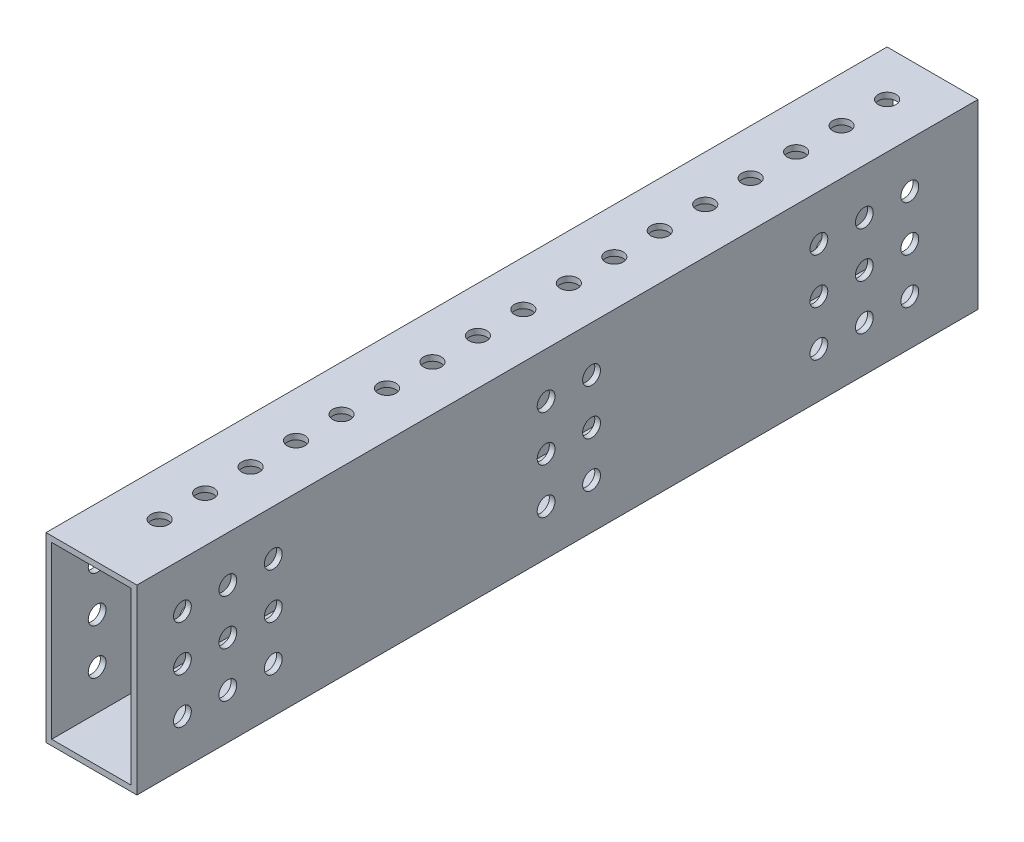
SolidWorks part; units mm, degrees
material "6061-T6 (SS)"
ref_plane "Front Plane" through (0, 0, 0) normal (0, 0, 1) x (1, 0, 0)
ref_plane "Top Plane" through (0, 0, 0) normal (0, 1, 0) x (1, 0, 0)
ref_plane "Right Plane" through (0, 0, 0) normal (1, 0, 0) x (0, 0, -1)
sketch "Sketch1" plane through (0, 0, 0) normal (1, 0, 0) x (0, 0, -1)
  line L0 (12.7, 50.8) -> (12.7, 0) construction
  line L1 (0, 0) -> (234.95, 0)
  line L2 (0, 0) -> (0, 50.8)
  line L3 (0, 50.8) -> (234.95, 50.8)
  line L4 (234.95, 0) -> (234.95, 50.8)
  line L5 (12.7, 12.7) -> (25.4, 12.7) construction
  circle A0 centre (12.7, 25.4) radius 2.4892
  circle A1 centre (12.7, 38.1) radius 2.4892
  circle A2 centre (12.7, 12.7) radius 2.4892
  circle A3 centre (25.4, 12.7) radius 2.4892
  circle A4 centre (25.4, 25.4) radius 2.4892
  circle A5 centre (25.4, 38.1) radius 2.4892
  circle A6 centre (38.1, 12.7) radius 2.4892
  circle A7 centre (38.1, 25.4) radius 2.4892
  circle A8 centre (38.1, 38.1) radius 2.4892
  circle A24 centre (114.3, 12.7) radius 2.4892
  circle A25 centre (114.3, 25.4) radius 2.4892
  circle A26 centre (114.3, 38.1) radius 2.4892
  circle A27 centre (127, 12.7) radius 2.4892
  circle A28 centre (127, 25.4) radius 2.4892
  circle A29 centre (127, 38.1) radius 2.4892
  circle A42 centre (190.5, 12.7) radius 2.4892
  circle A43 centre (190.5, 25.4) radius 2.4892
  circle A44 centre (190.5, 38.1) radius 2.4892
  circle A45 centre (203.2, 12.7) radius 2.4892
  circle A46 centre (203.2, 25.4) radius 2.4892
  circle A47 centre (203.2, 38.1) radius 2.4892
  circle A48 centre (215.9, 12.7) radius 2.4892
  circle A49 centre (215.9, 25.4) radius 2.4892
  circle A50 centre (215.9, 38.1) radius 2.4892
  circle A51 centre (50.8, 38.1) radius 2.4892 [skipped]
  circle A52 centre (50.8, 25.4) radius 2.4892 [skipped]
  circle A53 centre (50.8, 12.7) radius 2.4892 [skipped]
  circle A54 centre (63.5, 12.7) radius 2.4892 [skipped]
  circle A55 centre (63.5, 25.4) radius 2.4892 [skipped]
  circle A56 centre (63.5, 38.1) radius 2.4892 [skipped]
  circle A57 centre (76.2, 38.1) radius 2.4892 [skipped]
  circle A58 centre (76.2, 25.4) radius 2.4892 [skipped]
  circle A59 centre (76.2, 12.7) radius 2.4892 [skipped]
  circle A60 centre (88.9, 12.7) radius 2.4892 [skipped]
  circle A61 centre (88.9, 25.4) radius 2.4892 [skipped]
  circle A62 centre (88.9, 38.1) radius 2.4892 [skipped]
  circle A63 centre (101.6, 38.1) radius 2.4892 [skipped]
  circle A64 centre (101.6, 25.4) radius 2.4892 [skipped]
  circle A65 centre (101.6, 12.7) radius 2.4892 [skipped]
  circle A66 centre (139.7, 38.1) radius 2.4892 [skipped]
  circle A67 centre (139.7, 25.4) radius 2.4892 [skipped]
  circle A68 centre (139.7, 12.7) radius 2.4892 [skipped]
  circle A69 centre (152.4, 12.7) radius 2.4892 [skipped]
  circle A70 centre (152.4, 25.4) radius 2.4892 [skipped]
  circle A71 centre (152.4, 38.1) radius 2.4892 [skipped]
  circle A72 centre (165.1, 38.1) radius 2.4892 [skipped]
  circle A73 centre (165.1, 25.4) radius 2.4892 [skipped]
  circle A74 centre (165.1, 12.7) radius 2.4892 [skipped]
  circle A75 centre (177.8, 12.7) radius 2.4892 [skipped]
  circle A76 centre (177.8, 25.4) radius 2.4892 [skipped]
  circle A77 centre (177.8, 38.1) radius 2.4892 [skipped]
  dimension "D3" = 4.9784
  dimension "D1" = 50.8
  dimension "D2" = 234.95
  dimension "D4" = 12.7
  dimension "D5" = 12.7
  dimension "D6" = 12.7
  dimension "D8" = 12.7
  dimension "D7" = 17
extrude "Boss-Extrude1" add sketch "Sketch1" along normal blind 25.4
sketch "Sketch2" plane through (0, 0, 0) normal (0, 0, 1) x (1, 0, 0)
  line L8 (1.5875, 49.2125) -> (1.5875, 1.5875)
  line L9 (1.5875, 1.5875) -> (23.8125, 1.5875)
  line L10 (23.8125, 1.5875) -> (23.8125, 49.2125)
  line L11 (23.8125, 49.2125) -> (1.5875, 49.2125)
  line L12 (1.5875, 49.2125) -> (1.5875, 1.5875)
  line L13 (1.5875, 1.5875) -> (23.8125, 1.5875)
  line L14 (23.8125, 1.5875) -> (23.8125, 49.2125)
  line L15 (23.8125, 49.2125) -> (1.5875, 49.2125)
  dimension "D1" = 1.5875
extrude "Cut-Extrude1" cut sketch "Sketch2" against normal through all
sketch "Sketch3" plane through (0, 50.8, 0) normal (0, 1, 0) x (1, 0, 0)
  line L0 (12.7, 234.95) -> (12.7, 0) construction
  line L1 (25.4, 234.95) -> (0, 234.95) construction
  line L2 (25.4, 0) -> (0, 0) construction
  line L3 (12.7, 222.25) -> (12.7, 209.55) construction
  circle A0 centre (12.7, 222.25) radius 2.4892
  circle A1 centre (12.7, 209.55) radius 2.4892
  circle A2 centre (12.7, 196.85) radius 2.4892
  circle A3 centre (12.7, 184.15) radius 2.4892
  circle A4 centre (12.7, 171.45) radius 2.4892
  circle A5 centre (12.7, 158.75) radius 2.4892
  circle A6 centre (12.7, 146.05) radius 2.4892
  circle A7 centre (12.7, 133.35) radius 2.4892
  circle A8 centre (12.7, 120.65) radius 2.4892
  circle A9 centre (12.7, 107.95) radius 2.4892
  circle A10 centre (12.7, 95.25) radius 2.4892
  circle A11 centre (12.7, 82.55) radius 2.4892
  circle A12 centre (12.7, 69.85) radius 2.4892
  circle A13 centre (12.7, 57.15) radius 2.4892
  circle A14 centre (12.7, 44.45) radius 2.4892
  circle A15 centre (12.7, 31.75) radius 2.4892
  circle A16 centre (12.7, 19.05) radius 2.4892
  dimension "D1" = 4.9784
  dimension "D2" = 12.7
  dimension "D4" = 12.7
  dimension "D3" = 17
extrude "Cut-Extrude2" cut sketch "Sketch3" against normal through all
